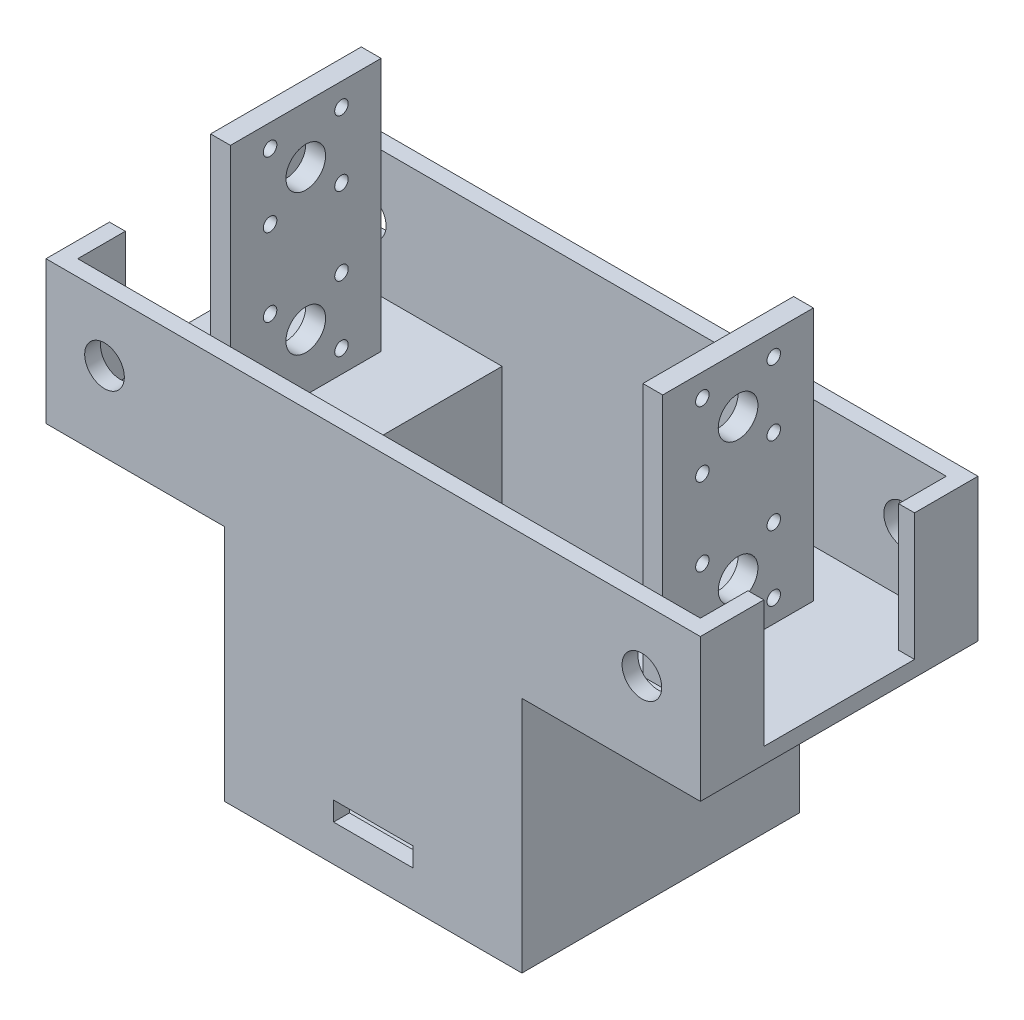
SolidWorks part; units mm, degrees
ref_plane "Front Plane" through (0, 0, 0) normal (0, 0, 1) x (1, 0, 0)
ref_plane "Top Plane" through (0, 0, 0) normal (0, 1, 0) x (1, 0, 0)
ref_plane "Right Plane" through (0, 0, 0) normal (1, 0, 0) x (0, 0, -1)
sketch "Sketch1" plane through (0, 0, 0) normal (0, 1, 0) x (1, 0, 0)
  line L0 (0, 0) -> (0, -14.43) construction
  line L1 (-37.5, 20) -> (37.5, 20)
  line L2 (-37.5, 20) -> (-37.5, -20)
  line L3 (-37.5, -20) -> (37.5, -20)
  line L4 (37.5, 20) -> (37.5, -20)
  line L5 (-37.5, 20) -> (37.5, -20) construction
  line L6 (-37.5, -20) -> (37.5, 20) construction
  line L7 (0, 0) -> (6.508, 0) construction
  line L8 (-2.5, 10) -> (2.5, 10)
  line L9 (-2.5, 10) -> (-2.5, -10)
  line L10 (-2.5, -10) -> (2.5, -10)
  line L11 (2.5, 10) -> (2.5, -10)
  line L12 (-2.5, 10) -> (2.5, -10) construction
  line L13 (-2.5, -10) -> (2.5, 10) construction
  circle A0 centre (-21, 0) radius 5
  circle A1 centre (-30, 8.25) radius 1.7
  circle A2 centre (-12, 8.25) radius 1.7
  circle A3 centre (-12, -8.25) radius 1.7
  circle A4 centre (-30, -8.25) radius 1.7
  circle A5 centre (12, 8.25) radius 1.7
  circle A6 centre (12, -8.25) radius 1.7
  circle A7 centre (21, 0) radius 5
  circle A8 centre (30, -8.25) radius 1.7
  circle A9 centre (30, 8.25) radius 1.7
  circle A10 centre (-30, -17.5) radius 1.1976
  circle A11 centre (-12, -17.5) radius 1.1976
  circle A12 centre (12, -17.5) radius 1.1976
  circle A13 centre (30, -17.5) radius 1.1976
  circle A14 centre (30, 17.5) radius 1.1976
  circle A15 centre (12, 17.5) radius 1.1976
  circle A16 centre (-12, 17.5) radius 1.1976
  circle A17 centre (-30, 17.5) radius 1.1976
  point P0 (0, 0)
  dimension "D3" = 10
  dimension "D4" = 21
  dimension "D5" = 8.25
  dimension "D6" = 9
  dimension "D9" = 5
  dimension "D11" = 20
  dimension "D12" = 7.5
  dimension "D13" = 25.5
  dimension "D14" = 7.5
  dimension "D15" = 2.5
  dimension "D1" = 75
  dimension "D2" = 40
  dimension "D10" = 20
  dimension "D7" = 2
  dimension "D8" = 2
  dimension "D16" = 2
extrude "Boss-Extrude1" add sketch "Sketch1" along normal blind 3
sketch "Sketch2" plane through (0, 3, 0) normal (0, 1, 0) x (1, 0, 0)
  line L0 (-37.5, 20) -> (-37.5, -20) construction
  line L1 (-33.5, 14) -> (33.5, 14)
  line L2 (-33.5, 14) -> (-33.5, -14)
  line L3 (-33.5, -14) -> (33.5, -14)
  line L4 (33.5, 14) -> (33.5, -14)
  line L5 (37.5, -20) -> (37.5, 20) construction
  line L6 (37.5, 20) -> (-37.5, 20) construction
  line L7 (-37.5, -20) -> (37.5, -20) construction
  dimension "D1" = 4
  dimension "D2" = 4
  dimension "D3" = 6
  dimension "D4" = 6
extrude "Cut-Extrude1" cut sketch "Sketch2" against normal through all both and the other way through all
sketch "Sketch3" plane through (0, 3, 0) normal (0, 1, 0) x (1, 0, 0)
  line L1 (37.5, 20) -> (-37.5, 20)
  line L2 (37.5, 20) -> (37.5, 35)
  line L3 (37.5, 35) -> (-37.5, 35)
  line L4 (-37.5, 20) -> (-37.5, 35)
  line L5 (-37.5, -20) -> (37.5, -20)
  line L6 (-37.5, -20) -> (-37.5, -35)
  line L7 (-37.5, -35) -> (37.5, -35)
  line L8 (37.5, -20) -> (37.5, -35)
  line L10 (-37.5, 20) -> (-33.5, 20)
  line L11 (-37.5, 20) -> (-37.5, -20)
  line L12 (-37.5, -20) -> (-33.5, -20)
  line L13 (-33.5, 20) -> (-33.5, -20)
  line L14 (37.5, 20) -> (33.5, 20)
  line L15 (37.5, 20) -> (37.5, -20)
  line L16 (37.5, -20) -> (33.5, -20)
  line L17 (33.5, 20) -> (33.5, -20)
  line M3 (-33.5, -14) -> (-33.5, 14)
  line M5 (33.5, 14) -> (33.5, -14)
  line M11 (37.5, -20) -> (37.5, 20)
  line M12 (37.5, 20) -> (-37.5, 20)
  line M13 (-37.5, 20) -> (-37.5, -20)
  line M14 (-37.5, -20) -> (37.5, -20)
  dimension "D1" = 15
  dimension "D2" = 15
extrude "Boss-Extrude3" add sketch "Sketch3" along normal blind 90 and the other way blind 3 contours L8 L5 L6 L7 M14 | L4 L1 L2 L3 M12 | L17 M12 M5 M14 M11 | L13 L1 M13 M14 M3
sketch "Sketch6" plane through (0, 3, 0) normal (0, 1, 0) x (1, 0, 0)
  line L0 (-37.5, -35) -> (37.5, -35) construction
  line L1 (-33.5, -20) -> (33.5, -20)
  line L2 (-33.5, -20) -> (-33.5, -31)
  line L3 (-33.5, -31) -> (33.5, -31)
  line L4 (33.5, -20) -> (33.5, -31)
  line L5 (33.5, 20) -> (-33.5, 20)
  line L6 (33.5, 20) -> (33.5, 31)
  line L7 (33.5, 31) -> (-33.5, 31)
  line L8 (-33.5, 20) -> (-33.5, 31)
  line L9 (37.5, 35) -> (-37.5, 35) construction
  dimension "D1" = 4
  dimension "D2" = 4
extrude "Cut-Extrude4" cut sketch "Sketch6" along normal through all
sketch "Sketch7" plane through (-37.5, 0, 0) normal (-1, 0, 0) x (0, 0, 1)
  line L0 (35, 0) -> (35, 93) construction
  line L1 (-35, 93) -> (35, 93)
  line L2 (-35, 93) -> (-35, 56)
  line L3 (-35, 56) -> (35, 56)
  line L4 (35, 93) -> (35, 56)
  dimension "D1" = 37
extrude "Boss-Extrude4" add sketch "Sketch7" along normal blind 45
ref_plane "Plane1" through (0, 0, 0) normal (1, 0, 0) x (0, 0, -1)
mirror "Mirror2" about plane through (0, 0, 0) normal (1, 0, 0) of "Boss-Extrude4"
sketch "Sketch8" plane through (0, 93, 0) normal (0, 1, 0) x (1, 0, 0)
  line L0 (-82.5, -35) -> (-82.5, 35) construction
  line L1 (-33.5, 31) -> (-78.5, 31)
  line L2 (-33.5, 31) -> (-33.5, -31)
  line L3 (-33.5, -31) -> (-78.5, -31)
  line L4 (-78.5, 31) -> (-78.5, -31)
  line L5 (33.5, -31) -> (78.5, -31)
  line L6 (33.5, -31) -> (33.5, 31)
  line L7 (33.5, 31) -> (78.5, 31)
  line L8 (78.5, -31) -> (78.5, 31)
  line L9 (82.5, -35) -> (82.5, 35) construction
  dimension "D1" = 4
  dimension "D2" = 4
extrude "Cut-Extrude6" cut sketch "Sketch8" against normal blind 29
sketch "Sketch9" plane through (-82.5, 0, 0) normal (-1, 0, 0) x (0, 0, 1)
  line L18 (-31, 64) -> (31, 64) construction
  line L19 (-19, 64) -> (19, 64)
  line L20 (-19, 64) -> (-19, 92.5)
  line L21 (-19, 92.5) -> (19, 92.5)
  line L22 (19, 64) -> (19, 92.5)
  line L25 (-31, 64) -> (-31, 93) construction
  dimension "D1" = 38
  dimension "D2" = 12
  dimension "D3" = 28.5
sketch "Sketch11" plane through (0, 0, 35) normal (0, 0, 1) x (1, 0, 0)
  line L0 (82.5, 56) -> (82.5, 93) construction
  line L1 (-82.5, 56) -> (-37.5, 56)
  line L2 (-82.5, 56) -> (-82.5, 60)
  line L3 (-82.5, 60) -> (-37.5, 60)
  line L4 (-37.5, 56) -> (-37.5, 60)
  line L5 (37.5, 56) -> (82.5, 56)
  line L6 (37.5, 56) -> (37.5, 60)
  line L7 (37.5, 60) -> (82.5, 60)
  line L8 (82.5, 56) -> (82.5, 60)
  line L11 (-78.5, 64) -> (-33.5, 64) construction
  line L12 (33.5, 64) -> (78.5, 64) construction
  dimension "D1" = 4
  dimension "D2" = 4
extrude "Cut-Extrude9" cut sketch "Sketch11" against normal through all
extrude "Cut-Extrude10" cut sketch "Sketch9" against normal through all
sketch "Sketch13" plane through (0, 64, 0) normal (0, 1, 0) x (1, 0, 0)
  line L0 (-78.5, 31) -> (-78.5, -31) construction
  line L1 (-57, 19) -> (-52, 19)
  line L2 (-57, 19) -> (-57, -19)
  line L3 (-57, -19) -> (-52, -19)
  line L4 (-52, 19) -> (-52, -19)
  line L7 (78.5, 31) -> (-78.5, 31) construction
  line L13 (-57, -19) -> (-57, 19)
  line L17 (-82.5, -19) -> (-107.5, -19)
  line L18 (-82.5, -19) -> (-82.5, 19)
  line L19 (-82.5, 19) -> (-107.5, 19)
  line L20 (-107.5, -19) -> (-107.5, 19)
  line L21 (-107.5, 19) -> (-61, 19)
  line L22 (-107.5, 19) -> (-107.5, -19)
  line L23 (-107.5, -19) -> (-61, -19)
  line L24 (-61, 19) -> (-61, -19)
  dimension "D1" = 21.5
  dimension "D2" = 5
  dimension "D3" = 38
  dimension "D4" = 12
  dimension "D5" = 25
  dimension "D6" = 46.5
extrude "Boss-Extrude5" add sketch "Sketch13" along normal blind 32 contours L4 L1 L2 L3
sketch "Sketch14" plane through (-57, 0, 0) normal (-1, 0, 0) x (0, 0, 1)
  line L0 (-19, 96) -> (-19, 64) construction
  line L1 (-19, 64) -> (19, 64) construction
  circle A0 centre (0, 78.25) radius 5
  circle A1 centre (-9, 86.2021) radius 1.7
  circle A2 centre (9, 86.2021) radius 1.7
  circle A3 centre (9, 69.7021) radius 1.7
  circle A4 centre (-9, 69.7021) radius 1.7
  dimension "D1" = 19
  dimension "D2" = 9
  dimension "D3" = 14.25
extrude "Cut-Extrude11" cut sketch "Sketch14" against normal blind 32
mirror "Mirror4" about plane through (0, 0, 0) normal (1, 0, 0) of "Boss-Extrude5", "Cut-Extrude11"
sketch "Sketch15" plane through (0, 93, 0) normal (0, 1, 0) x (1, 0, 0)
  line L1 (-82.5, 35) -> (82.5, 35)
  line L2 (-82.5, 35) -> (-82.5, -35)
  line L3 (-82.5, -35) -> (82.5, -35)
  line L4 (82.5, 35) -> (82.5, -35)
  line L5 (-78.5, 31) -> (78.5, 31)
  line L6 (-78.5, 31) -> (-78.5, -31)
  line L7 (-78.5, -31) -> (78.5, -31)
  line L8 (78.5, 31) -> (78.5, -31)
extrude "Boss-Extrude6" add sketch "Sketch15" along normal blind 3
sketch "Sketch16" plane through (0, 0, 35) normal (0, 0, 1) x (1, 0, 0)
  line L1 (-10, 14.0464) -> (10, 14.0464)
  line L2 (-10, 14.0464) -> (-10, 9.2258)
  line L3 (-10, 9.2258) -> (10, 9.2258)
  line L4 (10, 14.0464) -> (10, 9.2258)
  line L5 (-37.5, 0) -> (-37.5, 60) construction
  dimension "D1" = 20
  dimension "D2" = 27.5
extrude "Cut-Extrude12" cut sketch "Sketch16" against normal through all
sketch "Sketch18" plane through (0, 0, 35) normal (0, 0, 1) x (1, 0, 0)
  line L0 (57, 96) -> (57, 64) construction
  line L2 (33.5, 64) -> (78.5, 64) construction
  circle A0 centre (67.75, 80) radius 5
  dimension "D1" = 10.75
  dimension "D2" = 16
  dimension "D3" = 10
extrude "Cut-Extrude14" cut sketch "Sketch18" against normal through all
mirror "Mirror5" about plane through (0, 0, 0) normal (1, 0, 0) of "Cut-Extrude14"
mirror "Mirror6" about plane through (0, 96, 0) normal (0, 1, 0) of "Mirror4", "Boss-Extrude5", "Cut-Extrude11"
sketch "Sketch19" plane through (82.5, 0, 0) normal (1, 0, 0) x (0, 0, -1)
  line L0 (19, 128) -> (19, 64) construction
  line L1 (-19, 92.5) -> (19, 92.5)
  line L2 (-19, 92.5) -> (-19, 96)
  line L3 (-19, 96) -> (19, 96)
  line L4 (19, 92.5) -> (19, 96)
extrude "Cut-Extrude15" cut sketch "Sketch19" against normal blind 10
mirror "Mirror7" about plane through (0, 0, 0) normal (1, 0, 0) of "Cut-Extrude15"
